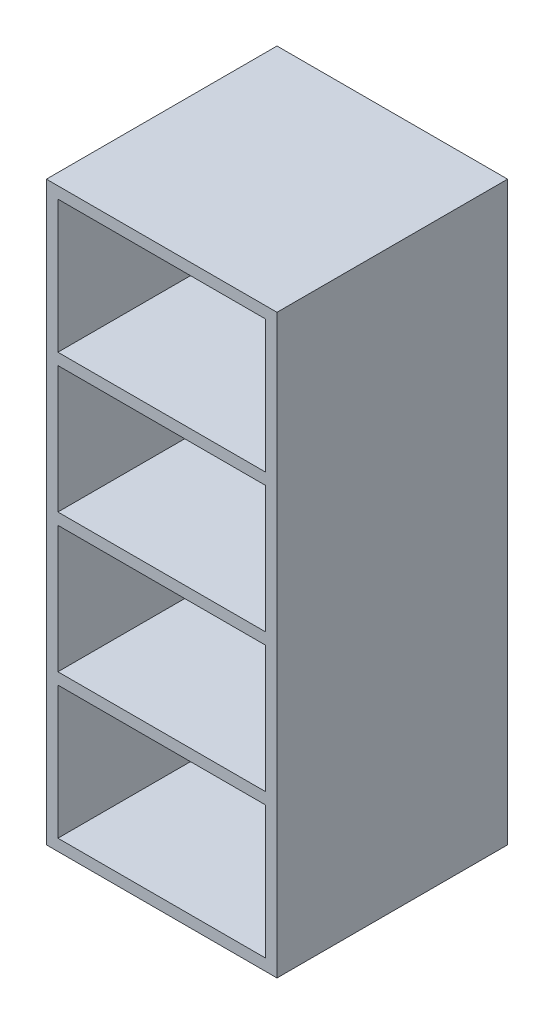
SolidWorks part; units mm, degrees
ref_plane "Front Plane" through (0, 0, 0) normal (0, 0, 1) x (1, 0, 0)
ref_plane "Top Plane" through (0, 0, 0) normal (0, 1, 0) x (1, 0, 0)
ref_plane "Right Plane" through (0, 0, 0) normal (1, 0, 0) x (0, 0, -1)
sketch "Sketch1" plane through (0, 0, 0) normal (0, 0, 1) x (1, 0, 0)
  line L0 (180, 980) -> (180, 20)
  line L1 (-200, 1000) -> (200, 1000)
  line L2 (-200, 1000) -> (-200, 0)
  line L3 (-200, 0) -> (200, 0)
  line L4 (200, 1000) -> (200, 0)
  line L5 (-180, 500) -> (180, 500) construction
  line L6 (-180, 740) -> (180, 740) construction
  line L7 (-180, 20) -> (180, 20)
  line L8 (-180, 980) -> (-180, 20)
  line L9 (-180, 980) -> (180, 980)
  line L10 (-180, 260) -> (180, 260) construction
  line L11 (-180, 730) -> (180, 730)
  line L12 (-180, 490) -> (180, 490)
  line L13 (-180, 250) -> (180, 250)
  line L14 (-180, 750) -> (180, 750)
  line L15 (-180, 510) -> (180, 510)
  line L16 (-180, 270) -> (180, 270)
  point P0 (0, 500)
  dimension "D1" = 400
  dimension "D2" = 1000
  dimension "D4" = 240
  dimension "D5" = 240
  dimension "D3" = 20
  dimension "D6" = 10
  dimension "D7" = 10
extrude "Boss-Extrude1" add sketch "Sketch1" along normal blind 400 contours L4 L1 L2 L3 L8 L9 L0 L7 | L14 L8 L11 L0 | L15 L8 L12 L0 | L16 L8 L13 L0
sketch "Sketch2" plane through (0, 0, 0) normal (0, 0, -1) x (-1, 0, 0)
  line L1 (-200, 1000) -> (200, 1000)
  line L2 (-200, 1000) -> (-200, 0)
  line L3 (-200, 0) -> (200, 0)
  line L4 (200, 1000) -> (200, 0)
extrude "Boss-Extrude2" add sketch "Sketch2" against normal blind 10
